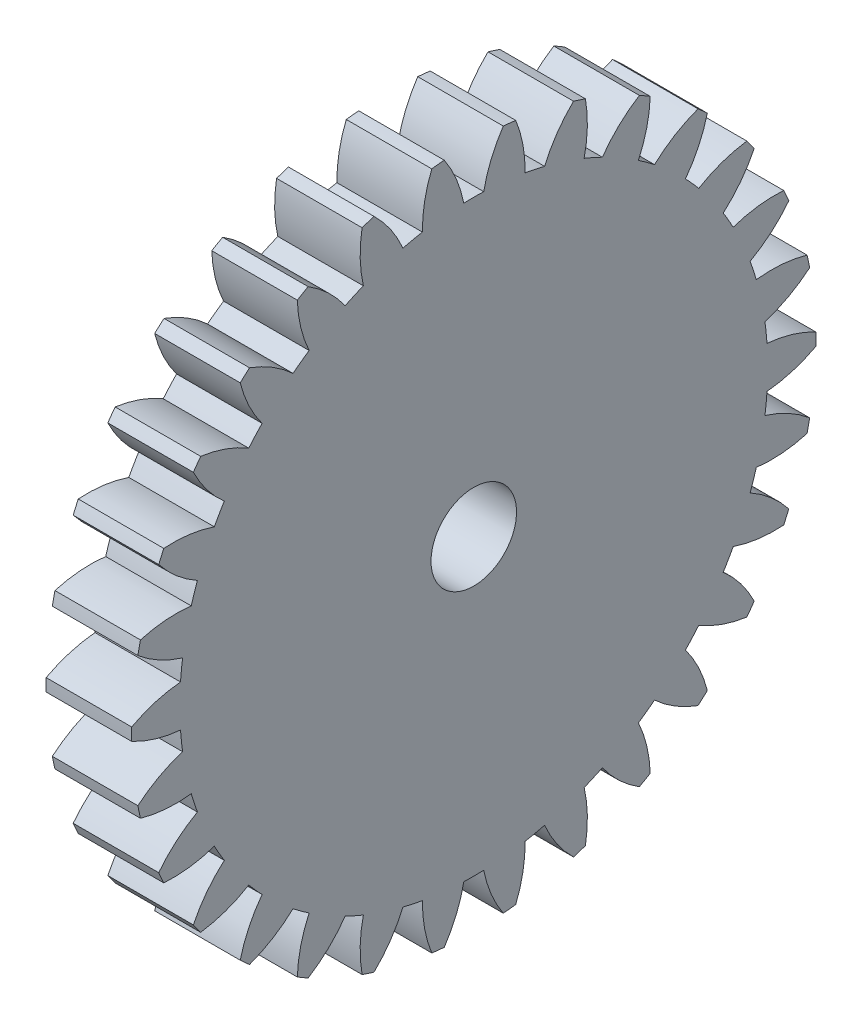
SolidWorks part; units mm, degrees
ref_plane "Plane1" through (0, 0, 0) normal (0, 0, 1) x (1, 0, 0)
ref_plane "Plane2" through (0, 0, 0) normal (0, 1, 0) x (1, 0, 0)
ref_plane "Plane3" through (0, 0, 0) normal (1, 0, 0) x (0, 0, -1)
sketch "HoldingSke" plane through (0, 0, 0) normal (0, 1, 0) x (1, 0, 0)
  line L0 (0, 0) -> (1.7321, -1)
  line L1 (-15, 0) -> (100, 0) construction
  line L2 (0, 0) -> (-2.1039, 2.3779)
  line L3 (0, 0) -> (-11.863, 4.5341)
  line L4 (0, 0) -> (7.479, 4.318)
  line L5 (0, 0) -> (-4.6848, -1.7473)
  line L6 (0, 0) -> (-1.6579, -1.1186)
  line L7 (-2.1039, 2.3779) -> (-1.0276, 7.2607)
  line L8 (-76.2, 54.61) -> (-75.9, 54.61)
  line L9 (-71.009, 38.7566) -> (-53.1078, 45.2721)
  line L10 (-76.2, 71.12) -> (104.1128, 71.12)
  line L11 (0, 0) -> (-2, 0)
  line L12 (-76.2, 101.6) -> (-76.181, 101.6)
  line L13 (24.9733, 27.94) -> (52.9518, 28.4284)
  line L14 (24.9733, 27.94) -> (24.9743, 27.94)
  line L15 (24.9733, 27.94) -> (100.4006, 29.5858)
  line L16 (-63.627, -0.5) -> (-12.827, -0.5)
  circle A0 centre (0, 0) radius 1
  circle A1 centre (0, 0) radius 2.5
  circle A2 centre (0, 0) radius 2.5
  circle A3 centre (0, 0) radius 1
  dimension "MHD" = 5
  dimension "Hub_dia" = 5
  dimension "Bore" = 2
  dimension "MBD" = 2
  dimension "Num_teeth" = 30
  dimension "Pitch" = 2
  dimension "Overall_len" = 5
  dimension "Show_teeth" = 30
  dimension "Thickness" = 2
  dimension "OAL" = 5.0001
  dimension "T_dim" = 0.3
  dimension "Ap" = 20
  dimension "H" = 19.05
  dimension "Pitch_radius" = 180.3128
  dimension "Width" = 2
  dimension "Backlash" = 0.019
  dimension "Addendum_fac" = 1
  dimension "Dedendum_fac" = 1.25
  dimension "Clearance_fac" = 0.25
  dimension "Dedendum_add" = 0.001
  dimension "Module" = 0.5
sketch "BasProSke" plane through (0, 0, 0) normal (0, 1, 0) x (1, 0, 0)
  line L0 (-10, 0) -> (60, 0) construction
  line L1 (0, 0) -> (0, 8)
  line L2 (0, 0) -> (2, 0)
  line L3 (2, 0) -> (2, 8)
  line L4 (2, 8) -> (0, 8)
  dimension "Thickness" = 2
  dimension "Diameter" = 16
revolve "Base-Revolve" add sketch "BasProSke" angle 360 about L0
sketch "TooCutSke" plane through (0, 0, 0) normal (1, 0, 0) x (0, 0, -1)
  line L1 (0, 0) -> (0, 107) construction
  line L2 (0, 0) -> (-0.4258, 7.4879) construction
  line L3 (0, 0) -> (-1.5661, 14.9007) construction
  line L4 (-0.4258, 7.4879) -> (-0.7831, 7.4504) construction
  arc A0 (0.2331, 6.87) -> (-0.2331, 6.87) centre (0, 0) ccw
  arc A1 (0.707, 7.9942) -> (-0.707, 7.9942) centre (0, 0) ccw
  circle A2 centre (0, 0) radius 7.5 construction
  circle A3 centre (0, 0) radius 7.0477 construction
  arc A4 (-0.2331, 6.87) -> (-0.707, 7.9942) centre (-3.1767, 6.2911) ccw
  arc A5 (0.707, 7.9942) -> (0.2331, 6.87) centre (3.1767, 6.2911) ccw
  dimension "Root_dia" = 13.748
  dimension "Overcut_dia" = 16.0508
  dimension "Pitch_dia" = 15
  dimension "Base_dia" = 14.0954
  dimension "Flank_rad" = 3
  dimension "Half_ang" = 6
  dimension "Half_CT" = 0.3593
extrude "ToothCut" cut sketch "TooCutSke" along normal through all
fillet "Breaks" [suppressed] radius 0.01
fillet "RootFillets" [suppressed] radius 0.126
pattern_circular "TeethCuts" count 30 every 12 about axis through (-10, 0, 0) along (1, 0, 0) of "ToothCut", "RootFillets", "Breaks"
sketch "HubNeaOneSke" plane through (0, 0, 0) normal (-1, 0, 0) x (0, 0, 1)
  circle A0 centre (0, 0) radius 2.5
  dimension "Diameter" = 5
extrude "HubNearOne" add sketch "HubNeaOneSke" along normal blind 3.0001
sketch "HubNeaBotSke" plane through (0, 0, 0) normal (-1, 0, 0) x (0, 0, 1)
  circle A0 centre (0, 0) radius 2.5
  dimension "Diameter" = 5
extrude "HubNearBoth" [suppressed] add sketch "HubNeaBotSke" along normal blind 1.5
ref_plane "FarPln" through (2, 0, 0) normal (1, 0, 0) x (0, 0, -1)
sketch "HubFarSke" plane through (2, 0, 0) normal (1, 0, 0) x (0, 0, -1)
  circle A0 centre (0, 0) radius 2.5
  dimension "Diameter" = 5
extrude "HubFar" [suppressed] add sketch "HubFarSke" along normal blind 1.5
sketch "BorSke" plane through (0, 0, 0) normal (1, 0, 0) x (0, 0, -1)
  circle A0 centre (0, 0) radius 1
  dimension "Diameter" = 2
extrude "Bore" cut sketch "BorSke" along normal mid plane 10.0001
sketch "KeySke" plane through (0, 0, 0) normal (1, 0, 0) x (0, 0, -1)
  line L0 (-0.4, 0) -> (-0.4, 1.3)
  line L1 (-0.4, 1.3) -> (0.4, 1.3)
  line L2 (0.4, 1.3) -> (0.4, 0)
  line L3 (0, 0) -> (0, 34) construction
  line L4 (-0.4, 0) -> (0.4, 0)
  dimension "Offset" = 1.3
  dimension "Width" = 0.8
extrude "Keyway" [suppressed] cut sketch "KeySke" along normal mid plane 10.0001
pattern_circular "Keyway2" [suppressed] count 2 every 90 about axis through (-10, 0, 0) along (1, 0, 0)
ref_plane "Plan1" through (1, 0, 0) normal (-1, 0, 0) x (0, 0, 1)
equation "' \"Module@HoldingSke\" = 6.35"
equation "' \"Num_teeth@HoldingSke\" = 12"
equation "' \"Ap@HoldingSke\" =  20"
equation "' \"Ap@HoldingSke\" = 20"
equation "' \"Width@HoldingSke\" = 0.5 * 25.4"
equation "' \"Hub_dia@HoldingSke\"= 1 * 25.4"
equation "' \"Hub_dia@HoldingSke\" = 1 * 25.4"
equation "' \"Overall_len@HoldingSke\" = 1.0 * 25.4"
equation "' \"Bore@HoldingSke\" = 0.75 * 25.4"
equation "' \"T_dim@HoldingSke\" = 0.1 * 25.4"
equation "' \"Width@KeySke\" = 0.25 * 25.4"
equation "' \"Show_teeth@HoldingSke\" = 13"
equation "' \"Backlash@HoldingSke\" = 0.009 * 25.4"
equation "' \"Addendum_fac@HoldingSke\" = 1.0"
equation "' \"Dedendum_fac@HoldingSke\" = 1.25"
equation "' \"Dedendum_add@HoldingSke\" = 0.00005 * 25.4"
equation "' \"Clearance_fac@HoldingSke\" = 0.25"
equation "\"Pitch@HoldingSke\" = 1 / \"Module@HoldingSke\""
equation "\"Overcut_dia@TooCutSke\" = (\"Num_teeth@HoldingSke\" + 2 * \"Addendum_fac@HoldingSke\") / \"Pitch@HoldingSke\" + 0.002 * 25.4"
equation "\"Pitch_dia@TooCutSke\" = \"Num_teeth@HoldingSke\" / \"Pitch@HoldingSke\""
equation "\"Base_dia@TooCutSke\" = \"Num_teeth@HoldingSke\" / \"Pitch@HoldingSke\" * cos((\"Ap@HoldingSke\"  * 3.14159265 / 180))"
equation "\"Root_dia@TooCutSke\" = (\"Num_teeth@HoldingSke\" + 2) / \"Pitch@HoldingSke\" - 2 * (\"Addendum_fac@HoldingSke\" + \"Dedendum_fac@HoldingSke\") / \"Pitch@HoldingSke\" - \"Dedendum_add@HoldingSke\" * 2"
equation "\"Half_ang@TooCutSke\" = 180 / \"Num_teeth@HoldingSke\""
equation "\"Half_CT@TooCutSke\" = \"Num_teeth@HoldingSke\" / \"Pitch@HoldingSke\" * sin((3.14159265 / 2 / \"Num_teeth@HoldingSke\")) / 2 - 7 * \"Backlash@HoldingSke\" / 4"
equation "\"Flank_rad@TooCutSke\" = \"Num_teeth@HoldingSke\" / \"Pitch@HoldingSke\" / 5"
equation "\"Radius@RootFillets\" = \"Clearance_fac@HoldingSke\" / \"Pitch@HoldingSke\" + \"Dedendum_add@HoldingSke\""
equation "\"Break_rad@Breaks\" = 0.02 / \"Pitch@HoldingSke\""
equation "\"Thickness@HoldingSke\" = \"Width@HoldingSke\""
equation "\"OAL@HoldingSke\" = \"Thickness@HoldingSke\""
equation "\"MHD@HoldingSke\" = (\"Num_teeth@HoldingSke\" + 2) / \"Pitch@HoldingSke\" - 2 * (\"Addendum_fac@HoldingSke\" + \"Dedendum_fac@HoldingSke\")  / \"Pitch@HoldingSke\" - \"Dedendum_add@HoldingSke\" * 2"
equation "\"MBD@HoldingSke\" = (\"Num_teeth@HoldingSke\" + 2) / \"Pitch@HoldingSke\" - 2 * (\"Addendum_fac@HoldingSke\" + \"Dedendum_fac@HoldingSke\")  / \"Pitch@HoldingSke\" - \"Dedendum_add@HoldingSke\" * 2 - 0.002 * 25.4"
equation "\"MHD@HoldingSke\" = ((sgn( \"MHD@HoldingSke\" - \"Hub_dia@HoldingSke\" )-1)*( \"MHD@HoldingSke\" - \"Hub_dia@HoldingSke\" ))/-2+ \"Hub_dia@HoldingSke\""
equation "\"MBD@HoldingSke\" = ((sgn( \"MBD@HoldingSke\" - \"Bore@HoldingSke\" )-1)*( \"MBD@HoldingSke\" - \"Bore@HoldingSke\" ))/-2+ \"Bore@HoldingSke\""
equation "\"OAL@HoldingSke\" = ((sgn( \"OAL@HoldingSke\" - \"Overall_len@HoldingSke\" )+1)*( \"OAL@HoldingSke\" - \"Overall_len@HoldingSke\" ))/2 + \"Overall_len@HoldingSke\" + 0.000002 * 25.4"
equation "\"Num_teeth@TeethCuts\" = int( \"Show_teeth@HoldingSke\" ) + 1"
equation "\"Num_teeth@TeethCuts\" = ((sgn( \"Num_teeth@TeethCuts\" - \"Num_teeth@HoldingSke\" )-1)*( \"Num_teeth@TeethCuts\" - \"Num_teeth@HoldingSke\" ))/-2+ \"Num_teeth@HoldingSke\""
equation "\"Num_teeth@TeethCuts\" = ((sgn( \"Num_teeth@TeethCuts\" - 2.0)+1)*( \"Num_teeth@TeethCuts\" - 2.0))/2 +2.0"
equation "\"Angle@TeethCuts\" = 360.0 / \"Num_teeth@HoldingSke\""
equation "\"Diameter@BasProSke\" = (\"Num_teeth@HoldingSke\" + 2 * \"Addendum_fac@HoldingSke\") / \"Pitch@HoldingSke\""
equation "\"Thickness@BasProSke\"  = \"Thickness@HoldingSke\""
equation "' \"Fillet_rad@BasProSke\" =  \"Thickness@HoldingSke\" * 0.05"
equation "' \"Fillet_rad@BasProSke\" = \"Thickness@HoldingSke\" * 0.05"
equation "\"MHD@HoldingSke\" = ((sgn( \"MHD@HoldingSke\" - \"Root_dia@TooCutSke\" )-1)*( \"MHD@HoldingSke\" - \"Root_dia@TooCutSke\" ))/-2+ \"Root_dia@TooCutSke\""
equation "\"Diameter@HubNeaOneSke\" = \"MHD@HoldingSke\""
equation "\"Length@HubNearOne\" = \"OAL@HoldingSke\" - \"Thickness@BasProSke\""
equation "\"Diameter@HubNeaBotSke\" = \"MHD@HoldingSke\""
equation "\"Length@HubNearBoth\" = ( \"OAL@HoldingSke\" - \"Thickness@BasProSke\" ) / 2.0"
equation "\"Thickness@FarPln\" = \"Thickness@BasProSke\""
equation "\"Diameter@HubFarSke\" = \"MHD@HoldingSke\""
equation "\"Length@HubFar\" = ( \"OAL@HoldingSke\" - \"Thickness@BasProSke\" ) / 2.0"
equation "\"Diameter@BorSke\" = \"MBD@HoldingSke\""
equation "\"D1@Bore\" = \"OAL@HoldingSke\" * 2.0"
equation "\"D1@Keyway\" = \"OAL@HoldingSke\" * 2.0"
equation "\"Offset@KeySke\" = \"T_dim@HoldingSke\" + \"MBD@HoldingSke\" / 2.0"
